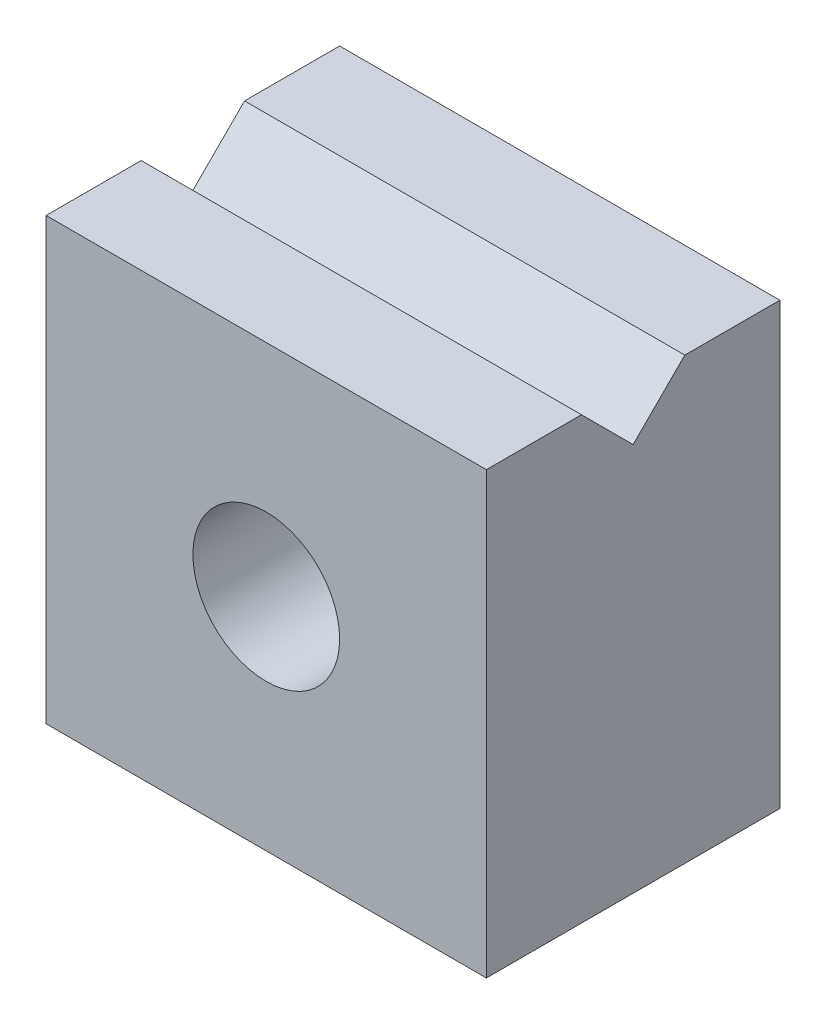
SolidWorks part; units mm, degrees
ref_plane "Front Plane" through (0, 0, 0) normal (0, 0, 1) x (1, 0, 0)
ref_plane "Top Plane" through (0, 0, 0) normal (0, 1, 0) x (1, 0, 0)
ref_plane "Right Plane" through (0, 0, 0) normal (1, 0, 0) x (0, 0, -1)
sketch "Sketch1" plane through (0, 0, 0) normal (0, 0, 1) x (1, 0, 0)
  line L1 (-9.525, -9.525) -> (9.525, -9.525)
  line L2 (-9.525, -9.525) -> (-9.525, 9.525)
  line L3 (-9.525, 9.525) -> (9.525, 9.525)
  line L4 (9.525, -9.525) -> (9.525, 9.525)
  line L5 (-9.525, -9.525) -> (9.525, 9.525) construction
  line L6 (-9.525, 9.525) -> (9.525, -9.525) construction
  point P0 (0, 0)
  dimension "D1" = 19.05
  dimension "D2" = 19.05
extrude "Boss-Extrude1" add sketch "Sketch1" along normal blind 12.7
sketch "Sketch2" plane through (0, 0, 12.7) normal (0, 0, 1) x (1, 0, 0)
  circle A0 centre (0, 0) radius 3.175
  dimension "D1" = 6.35
extrude "Cut-Extrude1" cut sketch "Sketch2" against normal blind 12.7
sketch "Sketch3" plane through (9.525, 0, 0) normal (1, 0, 0) x (0, 0, -1)
  line L0 (-6.35, 7.2898) -> (-4.1148, 9.525)
  line L1 (-12.7, 9.525) -> (0, 9.525) construction
  line L2 (-4.1148, 9.525) -> (-8.5852, 9.525)
  line L3 (-8.5852, 9.525) -> (-6.35, 7.2898)
  line L4 (0, -9.525) -> (0, 9.525) construction
  dimension "D1" = 45
  dimension "D2" = 90
  dimension "D3" = 2.2352
  dimension "D4" = 6.35
extrude "Cut-Extrude2" cut sketch "Sketch3" against normal through all
